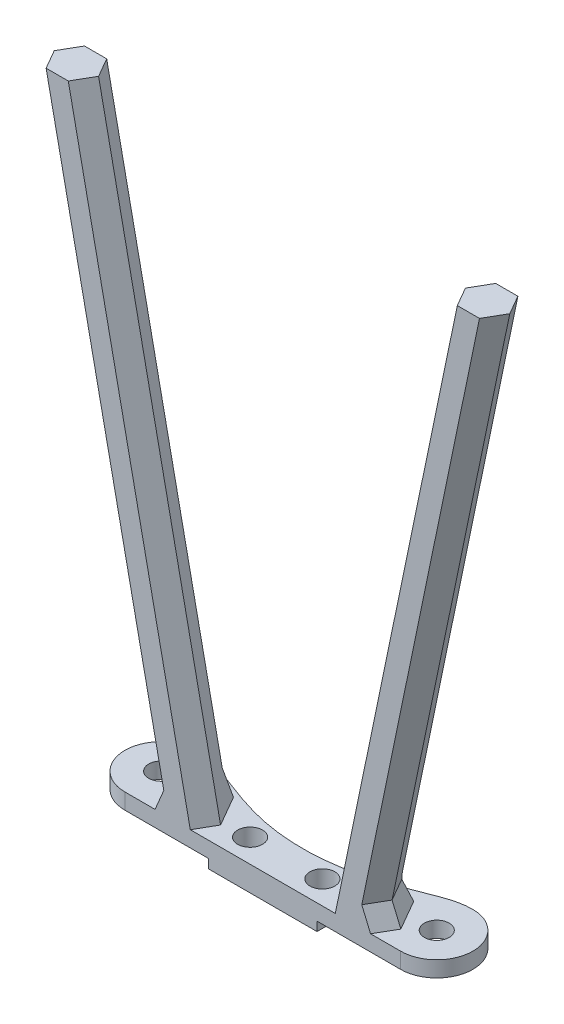
SolidWorks part; units mm, degrees
ref_plane "Front Plane" through (0, 0, 0) normal (0, 0, 1) x (1, 0, 0)
ref_plane "Top Plane" through (0, 0, 0) normal (0, 1, 0) x (1, 0, 0)
ref_plane "Right Plane" through (0, 0, 0) normal (1, 0, 0) x (0, 0, -1)
sketch "Sketch1" plane through (0, 0, 0) normal (0, 1, 0) x (1, 0, 0)
  line L0 (0, 0) -> (30.5, 0) construction
  line L1 (15.25, 0) -> (15.25, 7.3605) construction
  dimension "D1" = 30.5
sketch "Sketch2" plane through (0, 0, 0) normal (0, 1, 0) x (1, 0, 0)
  line L0 (0, 0) -> (30.5, 0) construction
  line L1 (0, 4) -> (30.5, 4)
  line L2 (0, -4) -> (30.5, -4)
  circle A0 centre (0, 0) radius 1.375
  circle A1 centre (30.5, 0) radius 1.375
  arc A2 (0, 4) -> (0, -4) centre (0, 0) ccw
  arc A3 (30.5, -4) -> (30.5, 4) centre (30.5, 0) ccw
  point P6 (15.25, 0)
  dimension "D1" = 2.75
  dimension "D2" = 2.75
  dimension "D3" = 4
extrude "Boss-Extrude1" add sketch "Sketch2" along normal blind 1.75
sketch "Sketch3" plane through (0, 1.75, 0) normal (0, 1, 0) x (1, 0, 0)
  line L2 (0, -4) -> (30.5, -4)
  line L3 (30.5, 4) -> (0, 4)
  line L4 (0, -4) -> (30.5, -4) construction
  line L5 (30.5, 4) -> (0, 4)
  arc A2 (0, 4) -> (0, -4) centre (0, 0) ccw
  arc A3 (30.5, -4) -> (30.5, 4) centre (30.5, 0) ccw
  arc A4 (0, 4) -> (0, -4) centre (0, 0) ccw construction
  arc A5 (30.5, -4) -> (30.5, 4) centre (30.5, 0) ccw construction
  spline S0 degree 3 poles (0, 4) (1.3926, 4) (4.7128, 2.7303) (11.2001, 0.2123) (19.2747, 0.2123) (25.8426, 2.7303) (29.0288, 4) (30.5, 4) knots 0 0 0 0 0.131329 0.332778 0.667222 0.868671 1 1 1 1
  point P5 (0, 0)
  point P9 (0, 0)
  point P11 (0, 0)
  point P14 (-1.5854, 1.38)
  dimension "D2" = 4
  dimension "D3" = 3
  dimension "D4" = 4
  dimension "D5" = 10
  dimension "D6" = 10
  dimension "D7" = 1
  dimension "D1" = 0
extrude "Cut-Extrude1" cut sketch "Sketch3" against normal blind 10
sketch "Sketch4" plane through (0, 1.75, 0) normal (0, 1, 0) x (1, 0, 0)
  line L7 (0, -4) -> (30.5, -4) construction
  line L8 (8.4537, -1.875) -> (7.2269, 0.25)
  line L9 (7.2269, 0.25) -> (4.7731, 0.25)
  line L10 (4.7731, 0.25) -> (3.5463, -1.875)
  line L11 (3.5463, -1.875) -> (4.7731, -4)
  line L12 (4.7731, -4) -> (7.2269, -4)
  line L13 (7.2269, -4) -> (8.4537, -1.875)
  circle A0 centre (6, -1.875) radius 2.125 construction
  dimension "D2" = 4.25
  dimension "D1" = 6
ref_plane "Plane1" through (0, 66.75, 0) normal (0, 1, 0) x (1, 0, 0)
sketch "Sketch5" plane through (0, 66.75, 0) normal (0, 1, 0) x (1, 0, 0)
  line L0 (0, -4) -> (30.5, -4) construction
  line L1 (-5.0463, -1.875) -> (-6.2731, 0.25)
  line L2 (-6.2731, 0.25) -> (-8.7269, 0.25)
  line L3 (-8.7269, 0.25) -> (-9.9537, -1.875)
  line L4 (-9.9537, -1.875) -> (-8.7269, -4)
  line L5 (-8.7269, -4) -> (-6.2731, -4)
  line L6 (-6.2731, -4) -> (-5.0463, -1.875)
  circle A0 centre (-7.5, -1.875) radius 2.125 construction
  dimension "D1" = 4.25
  dimension "D2" = 7.5
loft "Loft1" add profiles "Sketch4", "Sketch5"
chamfer "Chamfer1" distance 1.25 angle 70 3 edges
ref_plane "Plane2" through (15.25, 0, 0) normal (1, 0, 0) x (0, 0, -1)
mirror "Mirror1" about plane through (15.25, 0, 0) normal (1, 0, 0) of "Loft1", "Chamfer1"
sketch "Sketch6" plane through (0, 0, 0) normal (0, -1, 0) x (1, 0, 0)
  line L0 (9.25, 4) -> (9.25, -1.1867)
  line L1 (0, 4) -> (30.5, 4) construction
  line L3 (21.25, 4) -> (21.25, -1.1852)
  line L5 (9.25, 4) -> (21.25, 4)
  line L6 (30.5, 4) -> (0, 4)
  line L8 (15.25, -6.2483) -> (15.25, 6.2483) construction
  arc A2 (0, 4) -> (0, -4) centre (0, 0) ccw
  arc A3 (30.5, -4) -> (30.5, 4) centre (30.5, 0) ccw
  spline S0 degree 3 poles (0, -4) (1.3926, -4) (4.7128, -2.7303) (11.2001, -0.2123) (19.2747, -0.2123) (25.8426, -2.7303) (29.0288, -4) (30.5, -4) knots 0 0 0 0 0.131329 0.332778 0.667222 0.868671 1 1 1 1 construction
  spline S2 degree 3 poles (-1208.806, 7902.6869) (-69.3936, -29.3926) (-26.046, -14.6691) (11.2001, -0.2123) (19.2747, -0.2123) (56.0712, -14.3193) (80.2077, -28.613) (3396.5982, 7251.9906) knots -3.163574 -3.163574 -3.163574 -3.163574 0.131329 0.332778 0.667222 0.868671 4.070889 4.070889 4.070889 4.070889 only from (0, -4) to (30.5, -4)
  spline S3 degree 3 poles (9.25, -1.1867) (9.4988, -1.1205) (13.1359, -0.2123) (17.3368, -0.2123) (21.0012, -1.1196) (21.25, -1.1852) knots 0.308101 0.308101 0.308101 0.308101 0.332778 0.667222 0.691707 0.691707 0.691707 0.691707
  point P6 (15.25, 4)
  dimension "D1" = 12
  dimension "D2" = 0
extrude "Boss-Extrude2" add sketch "Sketch6" along normal blind 1
sketch "Sketch8" plane through (0, -1, 0) normal (0, -1, 0) x (1, 0, 0)
  line L0 (9.25, 1.4066) -> (21.25, 1.4074) construction
  line L1 (9.25, 4) -> (9.25, -1.1867) construction
  line L2 (21.25, -1.1852) -> (21.25, 4) construction
  circle A0 centre (11.25, 1.4068) radius 1.375
  circle A1 centre (19.25, 1.4073) radius 1.375
  dimension "D3" = 2.75
  dimension "D1" = 2
  dimension "D2" = 2
extrude "Cut-Extrude2" cut sketch "Sketch8" against normal through all
